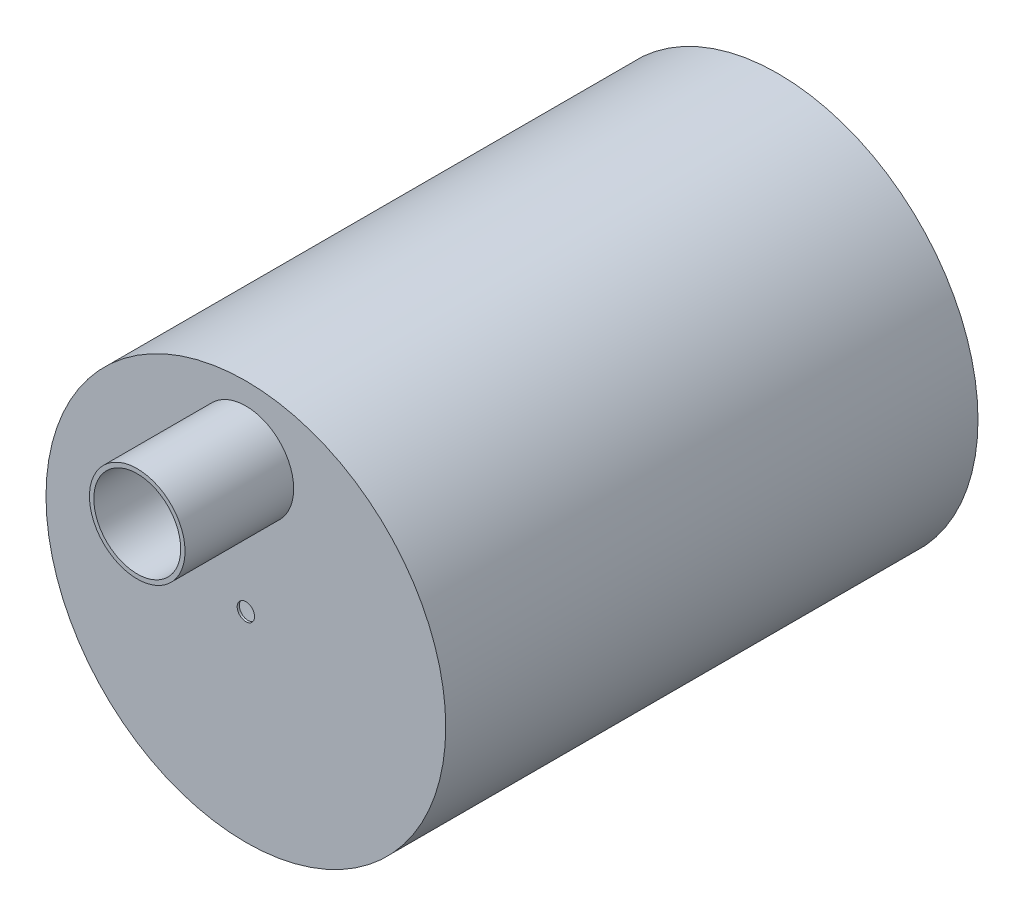
SolidWorks part; units mm, degrees
material "1060-H12"
ref_plane "Front Plane" through (0, 0, 0) normal (0, 0, 1) x (1, 0, 0)
ref_plane "Top Plane" through (0, 0, 0) normal (0, 1, 0) x (1, 0, 0)
ref_plane "Right Plane" through (0, 0, 0) normal (1, 0, 0) x (0, 0, -1)
sketch "Sketch1" plane through (0, 0, 0) normal (0, 0, 1) x (1, 0, 0)
  circle A0 centre (0, 0) radius 92
  circle A1 centre (0, 0) radius 90
  dimension "D1" = 184
  dimension "D2" = 2
extrude "Boss-Extrude1" add sketch "Sketch1" along normal blind 245
sketch "Sketch2" plane through (0, 0, 245) normal (0, 0, 1) x (1, 0, 0)
  line L0 (0, 0) -> (0, 92) construction
  circle A0 centre (0, 0) radius 90
  circle A1 centre (0, 0) radius 4
  circle A2 centre (0, 0) radius 92 construction
  circle A3 centre (0, 60) radius 20
  dimension "D1" = 8
  dimension "D2" = 40
  dimension "D3" = 60
extrude "Boss-Extrude2" add sketch "Sketch2" against normal blind 1
sketch "Sketch3" plane through (0, 0, 245) normal (0, 0, 1) x (1, 0, 0)
  circle A0 centre (0, 60) radius 20
  circle A1 centre (0, 60) radius 22
  dimension "D1" = 2
extrude "Boss-Extrude3" add sketch "Sketch3" along normal blind 50 separate body
